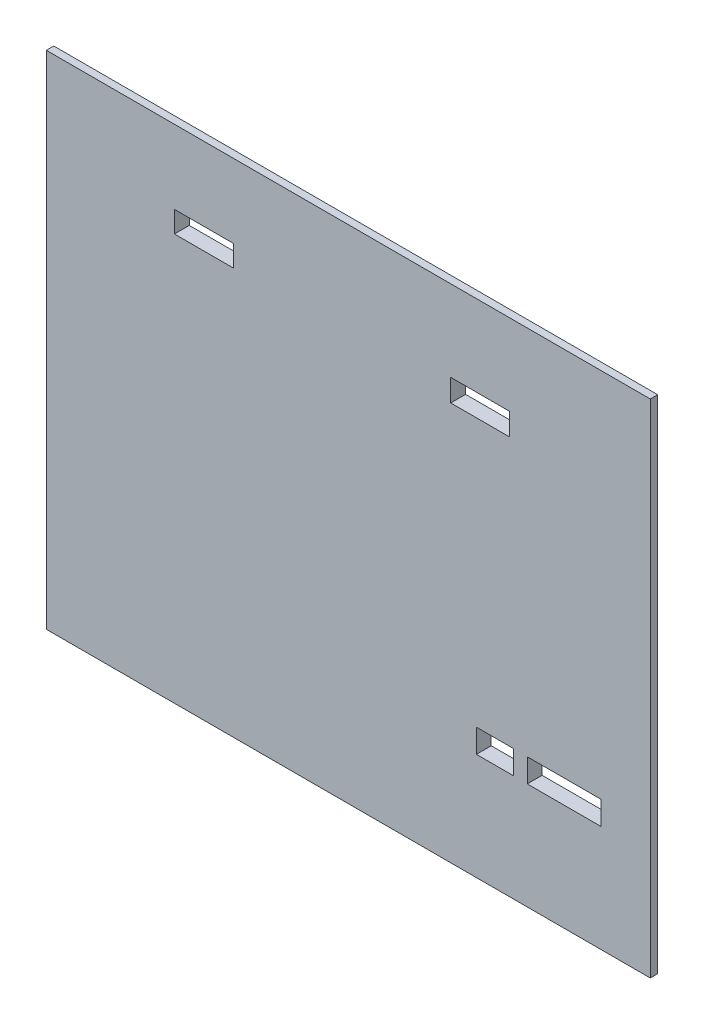
SolidWorks part; units mm, degrees
ref_plane "Front Plane" through (0, 0, 0) normal (0, 0, 1) x (1, 0, 0)
ref_plane "Top Plane" through (0, 0, 0) normal (0, 1, 0) x (1, 0, 0)
ref_plane "Right Plane" through (0, 0, 0) normal (1, 0, 0) x (0, 0, -1)
sketch "Sketch1" plane through (0, 0, 0) normal (0, 0, 1) x (1, 0, 0)
  line L1 (190.5, -31.5) -> (68.5, -31.5)
  line L2 (190.5, -31.5) -> (190.5, -132.8)
  line L3 (190.5, -132.8) -> (68.5, -132.8)
  line L4 (68.5, -31.5) -> (68.5, -132.8)
extrude "Boss-Extrude1" add sketch "Sketch1" along normal blind 3
sketch "Sketch2" plane through (190.5, 0, 0) normal (1, 0, 0) x (0, 0, -1)
  line L1 (0, -132.8) -> (-1.5, -132.8)
  line L2 (0, -132.8) -> (0, -130.7)
  line L3 (0, -130.7) -> (-1.5, -130.7)
  line L4 (-1.5, -132.8) -> (-1.5, -130.7)
  dimension "D1" = 1.5
  dimension "D2" = 2.1
extrude "Cut-Extrude2" cut sketch "Sketch2" against normal blind 130
sketch "Sketch3" plane through (190.5, 0, 0) normal (1, 0, 0) x (0, 0, -1)
  line L1 (0, -31.5) -> (-1.5, -31.5)
  line L2 (0, -31.5) -> (0, -33.6)
  line L3 (0, -33.6) -> (-1.5, -33.6)
  line L4 (-1.5, -31.5) -> (-1.5, -33.6)
  dimension "D1" = 1.5
  dimension "D2" = 2.1
extrude "Cut-Extrude3" cut sketch "Sketch3" against normal blind 123
sketch "Sketch4" plane through (0, -31.5, 0) normal (0, 1, 0) x (1, 0, 0)
  line L0 (68.5, -1.5) -> (190.5, -1.5) construction
  line L1 (68.5, 0) -> (70.6, 0)
  line L2 (68.5, 0) -> (68.5, -1.5)
  line L3 (68.5, -1.5) -> (70.6, -1.5)
  line L4 (70.6, 0) -> (70.6, -1.5)
  dimension "D1" = 1.5
  dimension "D2" = 2.1
extrude "Cut-Extrude4" cut sketch "Sketch4" against normal blind 123
sketch "Sketch5" plane through (0, -31.5, 0) normal (0, 1, 0) x (1, 0, 0)
  line L0 (68.5, -1.5) -> (190.5, -1.5) construction
  line L1 (190.5, 0) -> (188.4, 0)
  line L2 (190.5, 0) -> (190.5, -1.5)
  line L3 (190.5, -1.5) -> (188.4, -1.5)
  line L4 (188.4, 0) -> (188.4, -1.5)
  dimension "D1" = 1.5
  dimension "D2" = 2.1
extrude "Cut-Extrude5" cut sketch "Sketch5" against normal blind 123
sketch "Sketch6" plane through (0, 0, 3) normal (0, 0, 1) x (1, 0, 0)
  line L1 (165.6544, -106.5124) -> (180.5938, -106.5124)
  line L2 (165.6544, -106.5124) -> (165.6544, -111.2658)
  line L3 (165.6544, -111.2658) -> (180.5938, -111.2658)
  line L4 (180.5938, -106.5124) -> (180.5938, -111.2658)
sketch "Sketch7" plane through (0, 0, 3) normal (0, 0, 1) x (1, 0, 0)
  line L0 (162.875, -113.1) -> (162.875, -110.8) construction
  line L1 (162.875, -111.2337) -> (155.3772, -111.2337)
  line L2 (162.875, -111.2337) -> (162.875, -106.4742)
  line L3 (162.875, -106.4742) -> (155.3772, -106.4742)
  line L4 (155.3772, -111.2337) -> (155.3772, -106.4742)
  point P6 (162.875, -106.4742)
extrude "Cut-Extrude6" cut sketch "Sketch7" against normal blind 5
sketch "Sketch8" plane through (0, 0, 3) normal (0, 0, 1) x (1, 0, 0)
  line L1 (150.1944, -47.8735) -> (162.0433, -47.8735)
  line L2 (150.1944, -47.8735) -> (150.1944, -52.3497)
  line L3 (150.1944, -52.3497) -> (162.0433, -52.3497)
  line L4 (162.0433, -47.8735) -> (162.0433, -52.3497)
extrude "Cut-Extrude7" cut sketch "Sketch8" against normal blind 5
sketch "Sketch9" plane through (0, 0, 3) normal (0, 0, 1) x (1, 0, 0)
  line L0 (94.2574, -46.392) -> (94.4974, -46.392) construction
  line L1 (94.3774, -46.392) -> (106.2887, -46.392)
  line L2 (94.3774, -46.392) -> (94.3774, -50.7001)
  line L3 (94.3774, -50.7001) -> (106.2887, -50.7001)
  line L4 (106.2887, -46.392) -> (106.2887, -50.7001)
extrude "Cut-Extrude8" cut sketch "Sketch9" against normal blind 5
extrude "Cut-Extrude9" cut sketch "Sketch6" against normal blind 5
